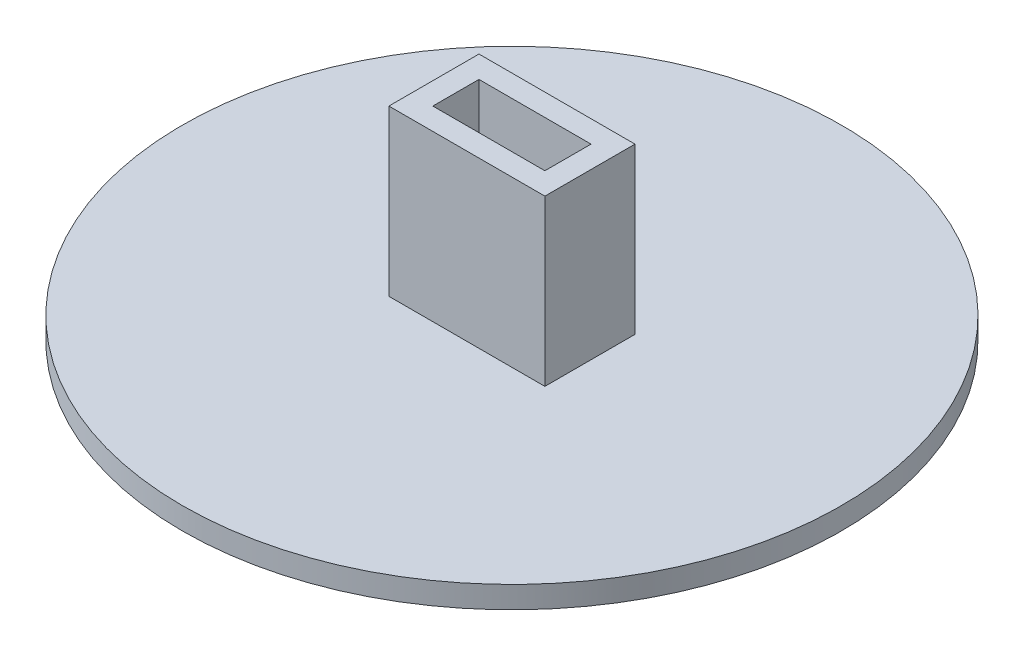
SolidWorks part; units mm, degrees
ref_plane "Plan de face" through (0, 0, 0) normal (0, 0, 1) x (1, 0, 0)
ref_plane "Plan de dessus" through (0, 0, 0) normal (0, 1, 0) x (1, 0, 0)
ref_plane "Plan de droite" through (0, 0, 0) normal (1, 0, 0) x (0, 0, -1)
sketch "Esquisse1" plane through (0, 0, 0) normal (0, 1, 0) x (1, 0, 0)
  circle A0 centre (0, 0) radius 30
  dimension "D1" = 60
extrude "Boss.-Extru.1" add sketch "Esquisse1" along normal blind 2
sketch "Esquisse2" plane through (0, 2, 0) normal (0, 1, 0) x (1, 0, 0)
  line L1 (-7.1, -4.1) -> (7.1, -4.1)
  line L2 (-7.1, -4.1) -> (-7.1, 4.1)
  line L3 (-7.1, 4.1) -> (7.1, 4.1)
  line L4 (7.1, -4.1) -> (7.1, 4.1)
  line L5 (-7.1, -4.1) -> (7.1, 4.1) construction
  line L6 (-7.1, 4.1) -> (7.1, -4.1) construction
  line L7 (-5.1, -2.1) -> (5.1, -2.1)
  line L8 (-5.1, -2.1) -> (-5.1, 2.1)
  line L9 (-5.1, 2.1) -> (5.1, 2.1)
  line L10 (5.1, -2.1) -> (5.1, 2.1)
  line L11 (-5.1, -2.1) -> (5.1, 2.1) construction
  line L12 (-5.1, 2.1) -> (5.1, -2.1) construction
  point P0 (0, 0)
  point P6 (0, 0)
  dimension "D1" = 8.2
  dimension "D2" = 14.2
  dimension "D3" = 2
  dimension "D4" = 2
extrude "Boss.-Extru.2" add sketch "Esquisse2" along normal blind 15
